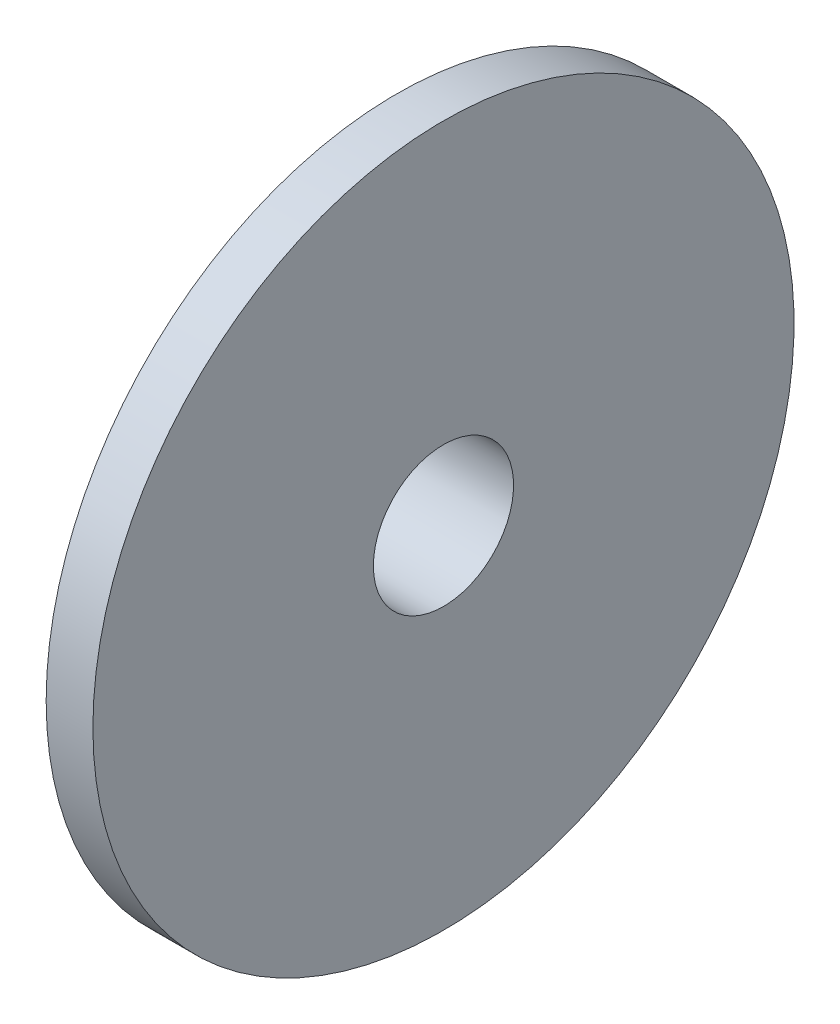
SolidWorks part; units mm, degrees
ref_plane "前视基准面" through (0, 0, 0) normal (0, 0, 1) x (1, 0, 0)
ref_plane "上视基准面" through (0, 0, 0) normal (0, 1, 0) x (1, 0, 0)
ref_plane "右视基准面" through (0, 0, 0) normal (1, 0, 0) x (0, 0, -1)
sketch "草图1" plane through (0, 0, 0) normal (0, 0, 1) x (1, 0, 0)
  line L0 (-9.1, 0) -> (4.0429, 0) construction
  line L1 (0, 9.1) -> (0, -7.5) construction
  line L2 (0, 1.5) -> (0, 7.5)
  line L3 (0, 7.5) -> (-1, 7.5)
  line L4 (-1, 7.5) -> (-1, 2.75)
  line L5 (-1, 2.75) -> (-3.5, 2.75)
  line L6 (-3.5, 2.75) -> (-3.5, 1.5)
  line L7 (-3.5, 1.5) -> (0, 1.5)
  dimension "D1" = 3
  dimension "D2" = 5.5
  dimension "D3" = 1
  dimension "D4" = 3.5
  dimension "D5" = 15
revolve "旋转1" add sketch "草图1" angle 360 about L0
chamfer "倒角1" distance 0.2 angle 45 2 edges at (-3.5, 0, 2.75) (-3.5, 0, 1.5)
